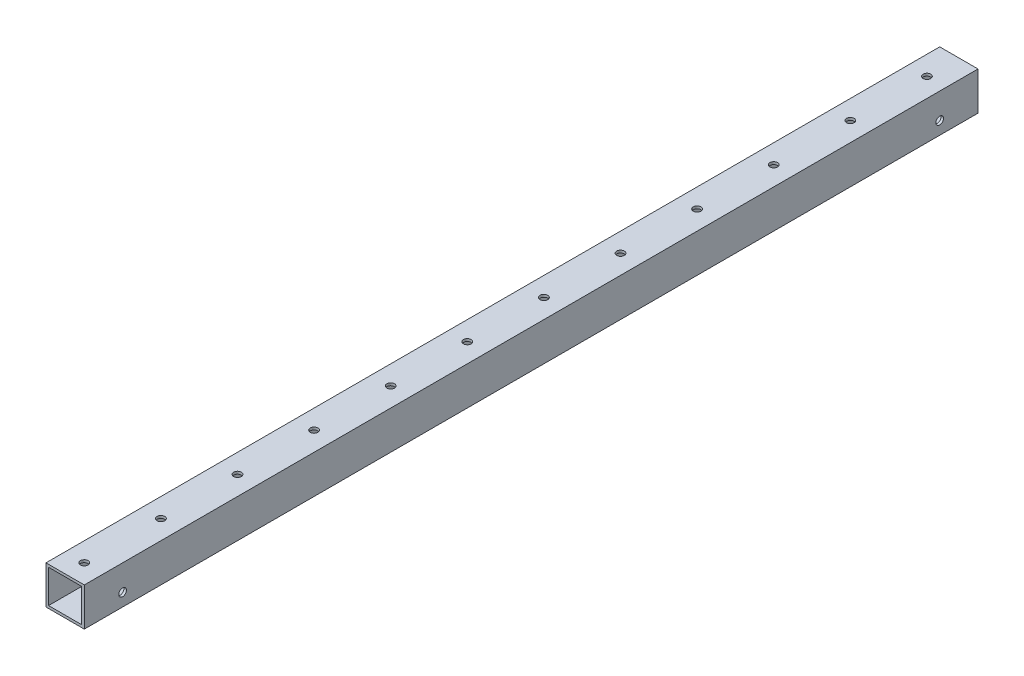
SolidWorks part; units mm, degrees
material "6061 合金"
ref_plane "前视基准面" through (0, 0, 0) normal (0, 0, 1) x (1, 0, 0)
ref_plane "上视基准面" through (0, 0, 0) normal (0, 1, 0) x (1, 0, 0)
ref_plane "右视基准面" through (0, 0, 0) normal (1, 0, 0) x (0, 0, -1)
sketch "草图1" plane through (0, 0, 0) normal (0, 0, 1) x (1, 0, 0)
  line L0 (-6.5, -6.5) -> (-6.5, 6.5)
  line L1 (-7.5, -7.5) -> (7.5, -7.5)
  line L2 (-7.5, -7.5) -> (-7.5, 7.5)
  line L3 (-7.5, 7.5) -> (7.5, 7.5)
  line L4 (7.5, -7.5) -> (7.5, 7.5)
  line L5 (-7.5, -7.5) -> (7.5, 7.5) construction
  line L6 (-7.5, 7.5) -> (7.5, -7.5) construction
  line L7 (-6.5, 6.5) -> (6.5, 6.5)
  line L8 (6.5, -6.5) -> (6.5, 6.5)
  line L9 (-6.5, -6.5) -> (6.5, -6.5)
  point P0 (0, 0)
  dimension "D1" = 15
  dimension "D2" = 1
extrude "凸台-拉伸1" add sketch "草图1" along normal mid plane 350
sketch "草图2" plane through (-7.5, 0, 0) normal (-1, 0, 0) x (0, 0, 1)
  line L0 (0, 0) -> (0, 7.5) construction
  line L1 (175, 7.5) -> (-175, 7.5) construction
  circle A1 centre (-160, -2.5) radius 1.5
  circle A2 centre (160, -2.5) radius 1.5
  circle A3 centre (-160, -2.5) radius 1.7 construction
extrude "切除-拉伸1" cut sketch "草图2" against normal mid plane 60
sketch "草图3" plane through (0, 7.5, 0) normal (0, 1, 0) x (1, 0, 0)
  circle A0 centre (0, -167.5) radius 1.5 construction
  circle A1 centre (0, -167.5) radius 1.5
extrude "切除-拉伸2" cut sketch "草图3" against normal blind 5
pattern_linear "阵列(线性)1" count 12 spacing 30 along (0, 0, -1) of "切除-拉伸2"
